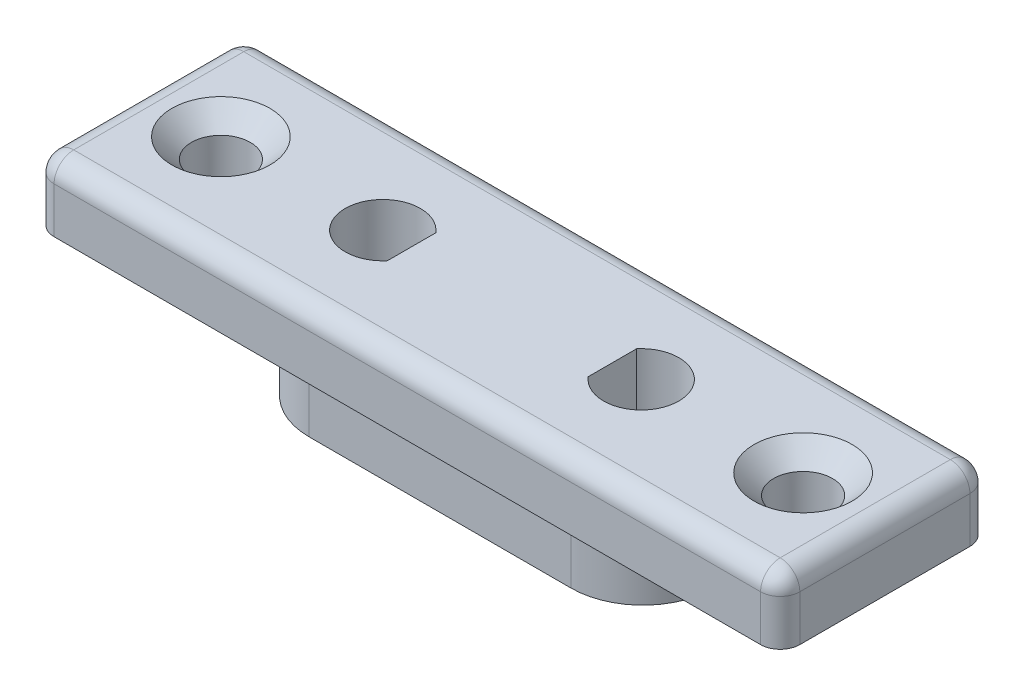
SolidWorks part; units mm, degrees
material "Полипропилен ГОСТ 26996-86"
ref_plane "Спереди" through (0, 0, 0) normal (0, 0, 1) x (1, 0, 0)
ref_plane "Сверху" through (0, 0, 0) normal (0, 1, 0) x (1, 0, 0)
ref_plane "Справа" through (0, 0, 0) normal (1, 0, 0) x (0, 0, -1)
sketch "Эскиз1" plane through (0, 0, 0) normal (0, 1, 0) x (1, 0, 0)
  line L0 (0, 0) -> (0, 16)
  line L1 (0, 16) -> (57, 16)
  line L2 (57, 16) -> (57, 0)
  line L3 (57, 0) -> (0, 0)
  dimension "D1" = 16
  dimension "D2" = 57
extrude "Бобышка-Вытянуть1" add sketch "Эскиз1" along normal blind 5
fillet "Скругление1" radius 1.5 8 edges at (0, 5, -8) (28.5, 5, -16) (57, 5, -8) (28.5, 5, 0) (0, 2.5, 0) (0, 2.5, -16) (57, 2.5, -16) (57, 2.5, 0)
sketch "Эскиз2" plane through (0, 5, 0) normal (0, 1, 0) x (1, 0, 0)
  line L0 (1.5, 1.5) -> (55.5, 1.5) construction
  line L5 (0, 1.5) -> (0, 14.5) construction
  line L9 (57, 14.5) -> (57, 1.5) construction
  line L15 (36.175, 9.8508) -> (36.175, 6.1492)
  line L16 (20.825, 9.8508) -> (20.825, 6.1492)
  arc A0 (36.175, 6.1492) -> (36.175, 9.8508) centre (38.375, 8) ccw
  arc A1 (20.825, 9.8508) -> (20.825, 6.1492) centre (18.625, 8) ccw
  dimension "D1" = 5.75
  dimension "D2" = 18.625
  dimension "D3" = 6.5
  dimension "D4" = 5.75
  dimension "D5" = 6.5
  dimension "D6" = 18.625
extrude "Вырез-Вытянуть1" cut sketch "Эскиз2" against normal blind 15
hole_wizard "Отверстие с зазором M41" positions "Эскиз5" profile "Эскиз6" hole size "M4" standard "ISO" end condition through all
sketch "Эскиз5" plane through (0, 5, 0) normal (0, 1, 0) x (1, 0, 0)
  line L0 (28.5, 14.5) -> (28.5, 1.5) construction
  line L1 (55.5, 14.5) -> (1.5, 14.5) construction
  line L2 (1.5, 1.5) -> (55.5, 1.5) construction
  point P0 (6.25, 8)
  point P3 (50.75, 8)
  dimension "D1" = 44.5
  dimension "D2" = 22.25
  dimension "D3" = 6.5
  dimension "D4" = 6.5
sketch "Эскиз6" plane through (6.25, 5, -8) normal (1, 0, 0) x (0, 0, 1)
  line L0 (0, 0) -> (0, 5)
  line L1 (0, 5) -> (2.25, 5)
  line L2 (2.25, 5) -> (2.25, 0)
  line L5 (2.25, 0) -> (0, 0)
  line L11 (0, -6.35) -> (0, 107.95) construction
  dimension "Диаметр сквозного отверстия" = 4.5
  dimension "Глубина сквозного отверстия" = 5
chamfer "Фаска1" distance 1.5 angle 45 2 edges at (50.75, 5, -5.75) (6.25, 5, -5.75)
sketch "Эскиз8" plane through (0, 0, 0) normal (0, -1, 0) x (1, 0, 0)
  line L0 (1.5, 0) -> (55.5, 0) construction
  line L5 (38.5, -2.5) -> (18.5, -2.5)
  line L7 (18.5, -13.5) -> (38.5, -13.5)
  line L8 (36.175, -6.1492) -> (36.175, -9.8508) construction
  line L9 (20.825, -9.8508) -> (20.825, -6.1492) construction
  line L10 (36.175, -6.1492) -> (36.175, -9.8508)
  line L11 (20.825, -9.8508) -> (20.825, -6.1492)
  arc A0 (38.5, -13.5) -> (38.5, -2.5) centre (38.5, -8) ccw
  arc A1 (18.5, -2.5) -> (18.5, -13.5) centre (18.5, -8) ccw
  arc A2 (36.175, -9.8508) -> (36.175, -6.1492) centre (38.375, -8) ccw construction
  arc A3 (20.825, -6.1492) -> (20.825, -9.8508) centre (18.625, -8) ccw construction
  arc A4 (36.175, -9.8508) -> (36.175, -6.1492) centre (38.375, -8) ccw
  arc A5 (20.825, -6.1492) -> (20.825, -9.8508) centre (18.625, -8) ccw
  dimension "D2" = 20
  dimension "D1" = 11
  dimension "D3" = 2.5
extrude "Бобышка-Вытянуть2" add sketch "Эскиз8" along normal blind 6
sketch "Эскиз9" plane through (0, -6, 0) normal (0, -1, 0) x (1, 0, 0)
  circle A0 centre (28.5, -8) radius 2.25
  dimension "D1" = 4.5
extrude "Вырез-Вытянуть2" cut sketch "Эскиз9" against normal blind 9.25
sketch "Эскиз10" plane through (0, -6, 0) normal (0, -1, 0) x (1, 0, 0)
  circle A0 centre (28.5, -8) radius 2.25
  circle A1 centre (28.5, -8) radius 4
  dimension "D1" = 8
  dimension "D2" = 4.5
extrude "Бобышка-Вытянуть3" add sketch "Эскиз10" along normal blind 0.1
